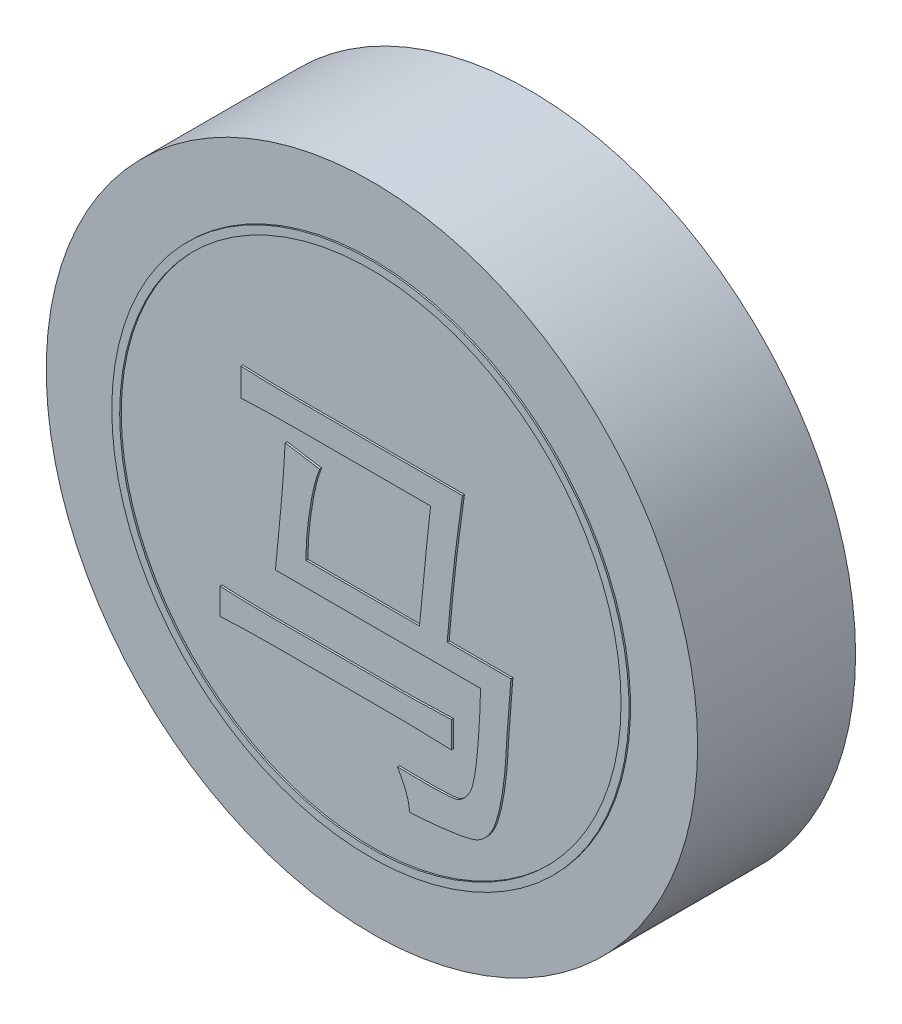
SolidWorks part; units mm, degrees
ref_plane "前视基准面" through (0, 0, 0) normal (0, 0, 1) x (1, 0, 0)
ref_plane "上视基准面" through (0, 0, 0) normal (0, 1, 0) x (1, 0, 0)
ref_plane "右视基准面" through (0, 0, 0) normal (1, 0, 0) x (0, 0, -1)
other "Configuration Table"
sketch "草图1" plane through (0, 0, 0) normal (0, 0, 1) x (1, 0, 0)
  circle A0 centre (0, 0) radius 16.5
  dimension "D1" = 33
extrude "Diameter33_Height8" add sketch "草图1" against normal blind 8
sketch "草图2" plane through (0, 0, 0) normal (0, 0, 1) x (1, 0, 0)
  text T0 "马" font "SimHei" height 12
extrude "Character_马" add sketch "草图2" along normal blind 0.1
sketch "草图3" plane through (0, 0, 0) normal (0, 0, 1) x (1, 0, 0)
  circle A0 centre (0, 0) radius 13.1
  circle A1 centre (0, 0) radius 12.7
extrude "Ink_ring" add sketch "草图3" along normal blind 0.08
